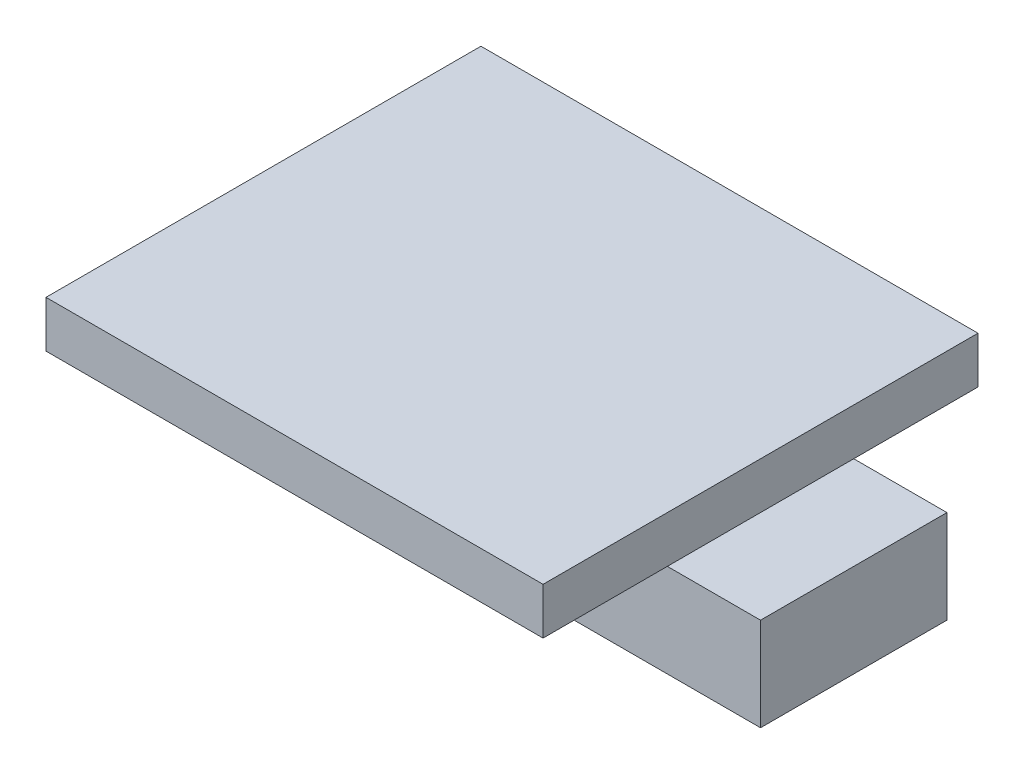
SolidWorks part; units mm, degrees
material "电源线路板"
ref_plane "前视基准面" through (0, 0, 0) normal (0, 0, 1) x (1, 0, 0)
ref_plane "上视基准面" through (0, 0, 0) normal (0, 1, 0) x (1, 0, 0)
ref_plane "右视基准面" through (0, 0, 0) normal (1, 0, 0) x (0, 0, -1)
sketch "草图1" plane through (0, 0, 0) normal (0, 1, 0) x (1, 0, 0)
  line L1 (-80, -70) -> (80, -70)
  line L2 (-80, -70) -> (-80, 70)
  line L3 (-80, 70) -> (80, 70)
  line L4 (80, -70) -> (80, 70)
  line L5 (-80, -70) -> (80, 70) construction
  line L6 (-80, 70) -> (80, -70) construction
  point P0 (0, 0)
  dimension "D1" = 160
  dimension "D2" = 140
extrude "凸台-拉伸1" add sketch "草图1" along normal blind 15
sketch "草图3" plane through (0, 0, 0) normal (0, -1, 0) x (1, 0, 0)
  line L0 (0, 0) -> (80, 0) construction
  line L2 (80, 70) -> (80, -70) construction
  line L4 (50, -30) -> (110, -30)
  line L5 (50, -30) -> (50, 30)
  line L6 (50, 30) -> (110, 30)
  line L7 (110, -30) -> (110, 30)
  line L8 (50, -30) -> (110, 30) construction
  line L9 (50, 30) -> (110, -30) construction
  dimension "D1" = 60
  dimension "D2" = 60
extrude "凸台-拉伸2" add sketch "草图3" along normal blind 30
